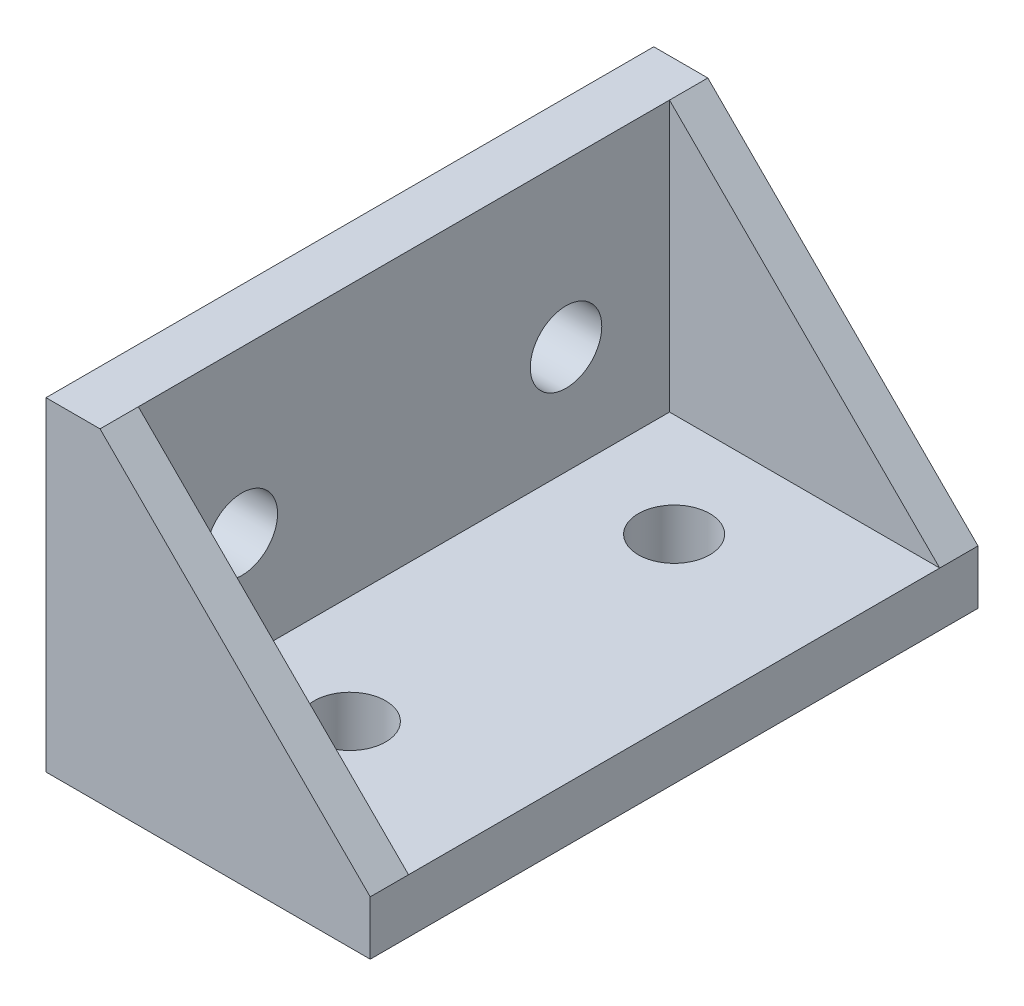
SolidWorks part; units mm, degrees
ref_plane "Front Plane" through (0, 0, 0) normal (0, 0, 1) x (1, 0, 0)
ref_plane "Top Plane" through (0, 0, 0) normal (0, 1, 0) x (1, 0, 0)
ref_plane "Right Plane" through (0, 0, 0) normal (1, 0, 0) x (0, 0, -1)
ref_plane "Plane_zm35_71" through (0, 0, -35.71) normal (0, 0, 1) x (1, 0, 0)
sketch "Sketch1" plane through (0, 0, -35.71) normal (0, 0, 1) x (1, 0, 0)
  line L0 (0, 0) -> (38.1, 0)
  line L1 (38.1, 0) -> (38.1, 6.35)
  line L2 (38.1, 6.35) -> (6.35, 38.1)
  line L3 (6.35, 38.1) -> (0, 38.1)
  line L4 (0, 38.1) -> (0, 0)
extrude "Body" add sketch "Sketch1" along normal blind 71.42
ref_plane "Plane_z31_21" through (0, 0, 31.21) normal (0, 0, 1) x (1, 0, 0)
sketch "Sketch2" plane through (0, 0, 31.21) normal (0, 0, 1) x (1, 0, 0)
  line L0 (6.35, 6.35) -> (48.1, 6.35)
  line L1 (48.1, 6.35) -> (6.35, 48.1)
  line L2 (6.35, 48.1) -> (6.35, 6.35)
extrude "Pocket" cut sketch "Sketch2" against normal blind 62.42
ref_plane "Plane_y6_35" through (0, 6.35, 0) normal (0, 1, 0) x (1, 0, 0)
sketch "Sketch3" plane through (0, 6.35, 0) normal (0, 1, 0) x (1, 0, 0)
  circle A0 centre (19.05, 19.05) radius 4.2
  circle A1 centre (19.05, -19.05) radius 4.2
extrude "HolesX" cut sketch "Sketch3" against normal blind 6.35
ref_plane "Plane_x6_35" through (6.35, 0, 0) normal (1, 0, 0) x (0, 0, -1)
sketch "Sketch4" plane through (6.35, 0, 0) normal (1, 0, 0) x (0, 0, -1)
  circle A0 centre (19.05, 19.05) radius 4.2
  circle A1 centre (-19.05, 19.05) radius 4.2
extrude "HolesY" cut sketch "Sketch4" against normal blind 6.35
